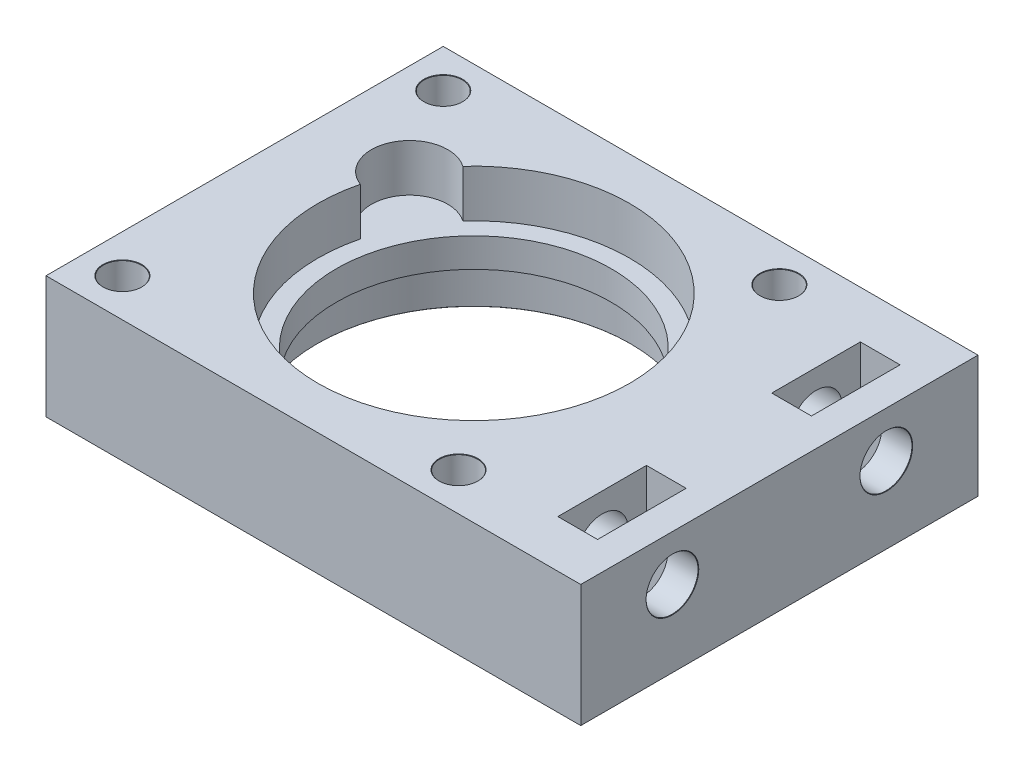
SolidWorks part; units mm, degrees
ref_plane "Front Plane" through (0, 0, 0) normal (0, 0, 1) x (1, 0, 0)
ref_plane "Top Plane" through (0, 0, 0) normal (0, 1, 0) x (1, 0, 0)
ref_plane "Right Plane" through (0, 0, 0) normal (1, 0, 0) x (0, 0, -1)
sketch "Sketch1" plane through (0, 0, 0) normal (0, 1, 0) x (1, 0, 0)
  line L1 (0, 0) -> (35, 0)
  line L2 (0, 0) -> (0, 26)
  line L3 (0, 26) -> (35, 26)
  line L4 (35, 0) -> (35, 26)
  dimension "D1" = 35
  dimension "D2" = 26
extrude "Boss-Extrude1" add sketch "Sketch1" along normal blind 8
hole_wizard "M3 Clearance Hole1" positions "Sketch2" profile "Sketch3" hole size "M3" standard "ANSI Metric"
sketch "Sketch2" plane through (35, 0, 0) normal (1, 0, 0) x (0, 0, -1)
  line L0 (0, 8) -> (26, 8) construction
  line L1 (0, 8) -> (0, 0) construction
  point P0 (6, 5)
  point P2 (20, 5)
  dimension "D1" = 3
  dimension "D2" = 3
  dimension "D3" = 14
  dimension "D4" = 6
sketch "Sketch3" plane through (35, 5, -6) normal (0, 1, 0) x (0, 0, -1)
  line L0 (0, 0) -> (0, 9.0215)
  line L1 (0, 9.0215) -> (1.7, 8)
  line L2 (1.7, 8) -> (1.7, 0.025)
  line L3 (1.7, 0.025) -> (1.725, 0)
  line L5 (1.725, 0) -> (0, 0)
  line L6 (-1.7, 0.025) -> (-1.725, 0) construction
  line L10 (0, 9.0215) -> (-1.7, 8) construction
  line L11 (0, -6.35) -> (0, 107.95) construction
  dimension "Hole Dia." = 3.4
  dimension "Hole Depth" = 8
  dimension "Near C'Sink Dia." = 3.45
  dimension "Near C'Sink Angle" = 90
  dimension "Drill Angle" = 118
hole_wizard "Tap Drill for M22x1.5 Tap1" positions "Sketch4" profile "Sketch5" hole size "M22x1.5" standard "ANSI Metric"
sketch "Sketch4" plane through (0, 0, 0) normal (0, -1, 0) x (-1, 0, 0)
  line L1 (0, 0) -> (-35, 0) construction
  line L3 (-35, 0) -> (-35, 26) construction
  point P0 (-15, 13)
  dimension "D2" = 13
  dimension "D1" = 20
sketch "Sketch5" plane through (15, 0, -13) normal (1, 0, 0) x (0, 0, -1)
  line L0 (0, 0) -> (0, 3)
  line L1 (0, 3) -> (10.25, 3)
  line L2 (10.25, 3) -> (10.25, 0.025)
  line L3 (10.25, 0.025) -> (10.275, 0)
  line L5 (10.275, 0) -> (0, 0)
  line L6 (-10.25, 0.025) -> (-10.275, 0) construction
  line L10 (0, 3) -> (-10.25, 3) construction
  line L11 (0, -6.35) -> (0, 107.95) construction
  dimension "Hole Dia." = 20.5
  dimension "Hole Depth" = 3
  dimension "Near C'Sink Dia." = 20.55
  dimension "Near C'Sink Angle" = 90
  dimension "Drill Angle" = 180
sketch "Sketch6" plane through (0, 8, 0) normal (0, 1, 0) x (1, 0, 0)
  line L1 (35, 26) -> (0, 26) construction
  line L2 (35, 0) -> (35, 26) construction
  circle A0 centre (15, 13) radius 10.2
  dimension "D1" = 20
  dimension "D3" = 20.4
  dimension "D2" = 13
extrude "Cut-Extrude1" cut sketch "Sketch6" against normal blind 3.1
sketch "Sketch7" plane through (0, 4.9, 0) normal (0, 1, 0) x (1, 0, 0)
  circle A0 centre (15, 13) radius 9
  dimension "D1" = 18
extrude "Cut-Extrude2" cut sketch "Sketch7" against normal through all
sketch "Sketch8" plane through (0, 8, 0) normal (0, 1, 0) x (1, 0, 0)
  line L0 (0, 26) -> (0, 0) construction
  circle A0 centre (6, 17.8) radius 2.5
  circle A1 centre (15, 13) radius 10.2 construction
  dimension "D1" = 5
  dimension "D2" = 6
extrude "Cut-Extrude3" cut sketch "Sketch8" against normal blind 3.1
hole_wizard "Tap Drill for M3x0.5 Tap1" positions "Sketch9" profile "Sketch10" hole size "M3x0.5" standard "ANSI Metric" end condition through all
sketch "Sketch9" plane through (0, 8, 0) normal (0, 1, 0) x (1, 0, 0)
  line L0 (0, 26) -> (0, 0) construction
  line L1 (35, 26) -> (0, 26) construction
  line L2 (0, 0) -> (35, 0) construction
  line L4 (35, 0) -> (35, 26) construction
  point P0 (2.5, 23.5)
  point P2 (24.5, 23.5)
  point P4 (24.5, 2.5)
  point P6 (2.5, 2.5)
  dimension "D1" = 2.5
  dimension "D2" = 2.5
  dimension "D3" = 2.5
  dimension "D4" = 2.5
  dimension "D5" = 2.5
  dimension "D6" = 22
  dimension "D7" = 22
  dimension "D8" = 2.5
  dimension "D9" = 10.5
sketch "Sketch10" plane through (2.5, 8, -23.5) normal (1, 0, 0) x (0, 0, 1)
  line L0 (0, 0) -> (0, 8)
  line L1 (0, 8) -> (1.25, 8)
  line L2 (1.25, 8) -> (1.25, 0.025)
  line L3 (1.25, 0.025) -> (1.275, 0)
  line L5 (1.275, 0) -> (0, 0)
  line L6 (-1.25, 0.025) -> (-1.275, 0) construction
  line L11 (0, -6.35) -> (0, 107.95) construction
  dimension "Thru Hole Dia." = 2.5
  dimension "Thru Hole Depth" = 8
  dimension "Near C'Sink Dia." = 2.55
  dimension "Near C'Sink Angle" = 90
sketch "Sketch11" plane through (0, 8, 0) normal (0, 1, 0) x (1, 0, 0)
  line L0 (35, 0) -> (35, 26) construction
  line L1 (30.4, 8.9) -> (33, 8.9)
  line L2 (30.4, 8.9) -> (30.4, 3.1)
  line L3 (30.4, 3.1) -> (33, 3.1)
  line L4 (33, 8.9) -> (33, 3.1)
  line L5 (0, 0) -> (35, 0) construction
  line L7 (33, 22.9) -> (30.4, 22.9)
  line L8 (33, 22.9) -> (33, 17.1)
  line L9 (33, 17.1) -> (30.4, 17.1)
  line L10 (30.4, 22.9) -> (30.4, 17.1)
  point P13 (33, 20)
  dimension "D1" = 5.8
  dimension "D2" = 2.6
  dimension "D3" = 2
  dimension "D4" = 3.1
  dimension "D5" = 2.6
  dimension "D6" = 5.8
  dimension "D7" = 2
  dimension "D8" = 20
extrude "Cut-Extrude4" cut sketch "Sketch11" against normal through all
equation "\"D4@Sketch2\"=(\"D2@Sketch1\"-\"D3@Sketch2\")/2"
equation "\"D2@Sketch4\"=\"D2@Sketch1\"/2"
equation "\"D4@Sketch11\"=\"D4@Sketch2\"-\"D1@Sketch11\"/2"
equation "\"D8@Sketch11\"=(\"D2@Sketch1\"-\"D3@Sketch2\")/2+\"D3@Sketch2\""
